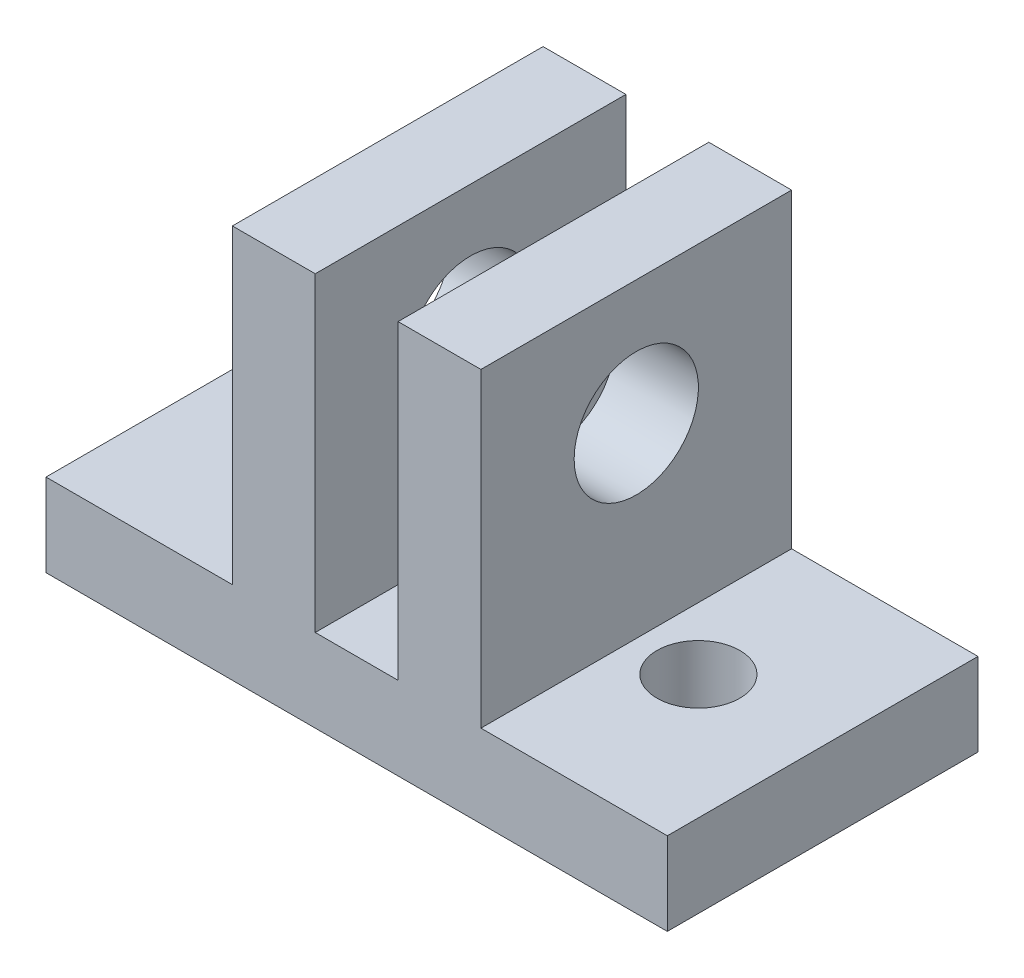
SolidWorks part; units mm, degrees
ref_plane "Спереди" through (0, 0, 0) normal (0, 0, 1) x (1, 0, 0)
ref_plane "Сверху" through (0, 0, 0) normal (0, 1, 0) x (1, 0, 0)
ref_plane "Справа" through (0, 0, 0) normal (1, 0, 0) x (0, 0, -1)
sketch "Эскиз1" plane through (0, 0, 0) normal (0, 1, 0) x (1, 0, 0)
  line L1 (0, 0) -> (30, 0)
  line L2 (0, 0) -> (0, 15)
  line L3 (0, 15) -> (30, 15)
  line L4 (30, 0) -> (30, 15)
  dimension "D1" = 15
  dimension "D2" = 30
extrude "Бобышка-Вытянуть1" add sketch "Эскиз1" along normal blind 4
sketch "Эскиз2" plane through (0, 4, 0) normal (0, 1, 0) x (1, 0, 0)
  line L0 (15, 15) -> (15, 0) construction
  line L3 (30, 15) -> (0, 15) construction
  line L4 (0, 0) -> (30, 0) construction
  line L6 (9, 15) -> (13, 15)
  line L7 (9, 15) -> (9, 0)
  line L8 (9, 0) -> (13, 0)
  line L9 (13, 15) -> (13, 0)
  line L10 (17, 15) -> (21, 15)
  line L11 (17, 15) -> (17, 0)
  line L12 (17, 0) -> (21, 0)
  line L13 (21, 15) -> (21, 0)
  dimension "D1" = 4
  dimension "D2" = 4
  dimension "D3" = 2
  dimension "D4" = 2
extrude "Бобышка-Вытянуть2" add sketch "Эскиз2" along normal blind 15
sketch "Эскиз3" plane through (0, 0, 0) normal (0, -1, 0) x (1, 0, 0)
  line L0 (0, -7.5) -> (30, -7.5) construction
  line L1 (0, -15) -> (0, 0) construction
  line L2 (30, 0) -> (30, -15) construction
  circle A0 centre (6, -7.5) radius 2
  circle A1 centre (24, -7.5) radius 2
  dimension "D1" = 4
  dimension "D2" = 4
  dimension "D3" = 6
  dimension "D4" = 6
extrude "Вырез-Вытянуть1" cut sketch "Эскиз3" against normal blind 15
sketch "Эскиз4" plane through (9, 0, 0) normal (-1, 0, 0) x (0, 0, 1)
  line L0 (-7.5, 19) -> (-7.5, 5.5292) construction
  line L1 (-15, 19) -> (0, 19) construction
  circle A0 centre (-7.5, 13) radius 3
  dimension "D1" = 6
extrude "Вырез-Вытянуть2" cut sketch "Эскиз4" against normal blind 15
